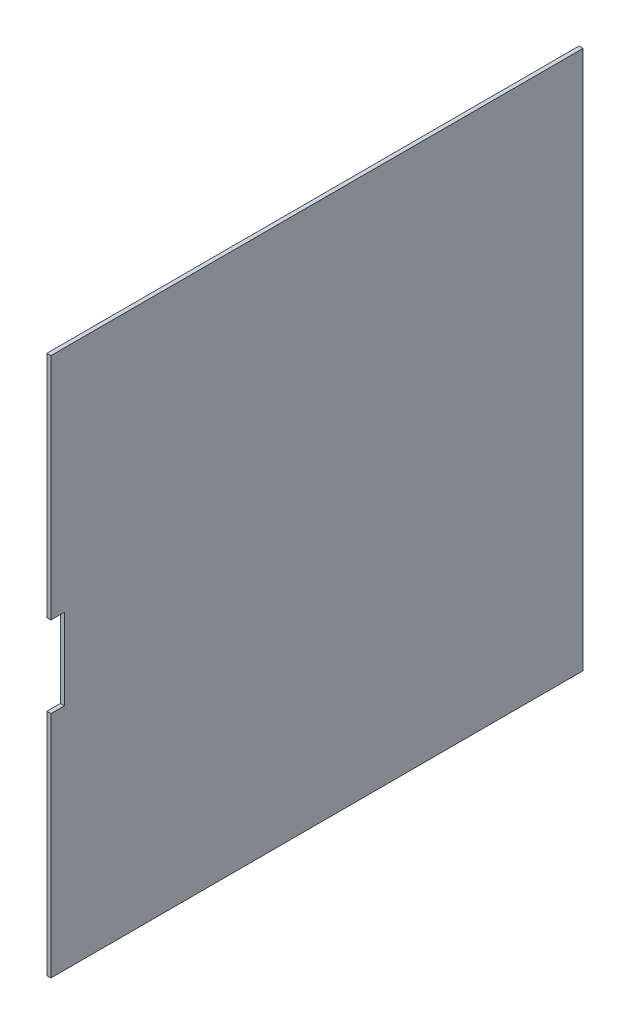
SolidWorks part; units mm, degrees
ref_plane "前基準面" through (0, 0, 0) normal (0, 0, 1) x (1, 0, 0)
ref_plane "上基準面" through (0, 0, 0) normal (0, 1, 0) x (1, 0, 0)
ref_plane "右基準面" through (0, 0, 0) normal (1, 0, 0) x (0, 0, -1)
sketch "草圖1" plane through (0, 0, 0) normal (1, 0, 0) x (0, 0, -1)
  line L1 (-197, 199.5) -> (197, 199.5)
  line L2 (-197, 199.5) -> (-197, -199.5)
  line L3 (-197, -199.5) -> (197, -199.5)
  line L4 (197, 199.5) -> (197, -199.5)
  line L5 (-197, 199.5) -> (197, -199.5) construction
  line L6 (-197, -199.5) -> (197, 199.5) construction
  point P0 (0, 0)
  dimension "D1" = 399
  dimension "398" = 394
extrude "填料-伸長1" add sketch "草圖1" along normal blind 3
sketch "草圖2" plane through (3, 0, 0) normal (1, 0, 0) x (0, 0, -1)
  line L0 (-197, 199.5) -> (-197, -199.5) construction
  line L1 (-197, 30) -> (-187, 30)
  line L2 (-197, 30) -> (-197, -30)
  line L3 (-197, -30) -> (-187, -30)
  line L4 (-187, 30) -> (-187, -30)
  line L5 (1.65, 0) -> (-1.65, 0) construction
  dimension "D1" = 10
  dimension "D2" = 60
  dimension "D3" = 30
extrude "除料-伸長1" cut sketch "草圖2" against normal through all
